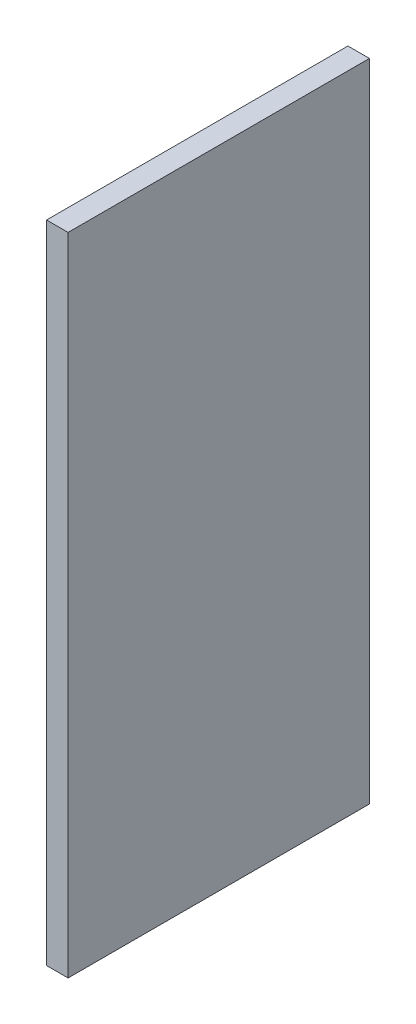
SolidWorks part; units mm, degrees
material "Glas"
ref_plane "Ebene vorne" through (0, 0, 0) normal (0, 0, 1) x (1, 0, 0)
ref_plane "Ebene oben" through (0, 0, 0) normal (0, 1, 0) x (1, 0, 0)
ref_plane "Ebene rechts" through (0, 0, 0) normal (1, 0, 0) x (0, 0, -1)
sketch "Skizze1" plane through (0, 0, 0) normal (1, 0, 0) x (0, 0, -1)
  line L1 (-35, 75) -> (35, 75)
  line L2 (-35, 75) -> (-35, -75)
  line L3 (-35, -75) -> (35, -75)
  line L4 (35, 75) -> (35, -75)
  line L5 (-35, 75) -> (35, -75) construction
  line L6 (-35, -75) -> (35, 75) construction
  point P0 (0, 0)
  dimension "D1" = 150
  dimension "D2" = 70
extrude "Aufsatz-Linear austragen1" add sketch "Skizze1" along normal blind 5
